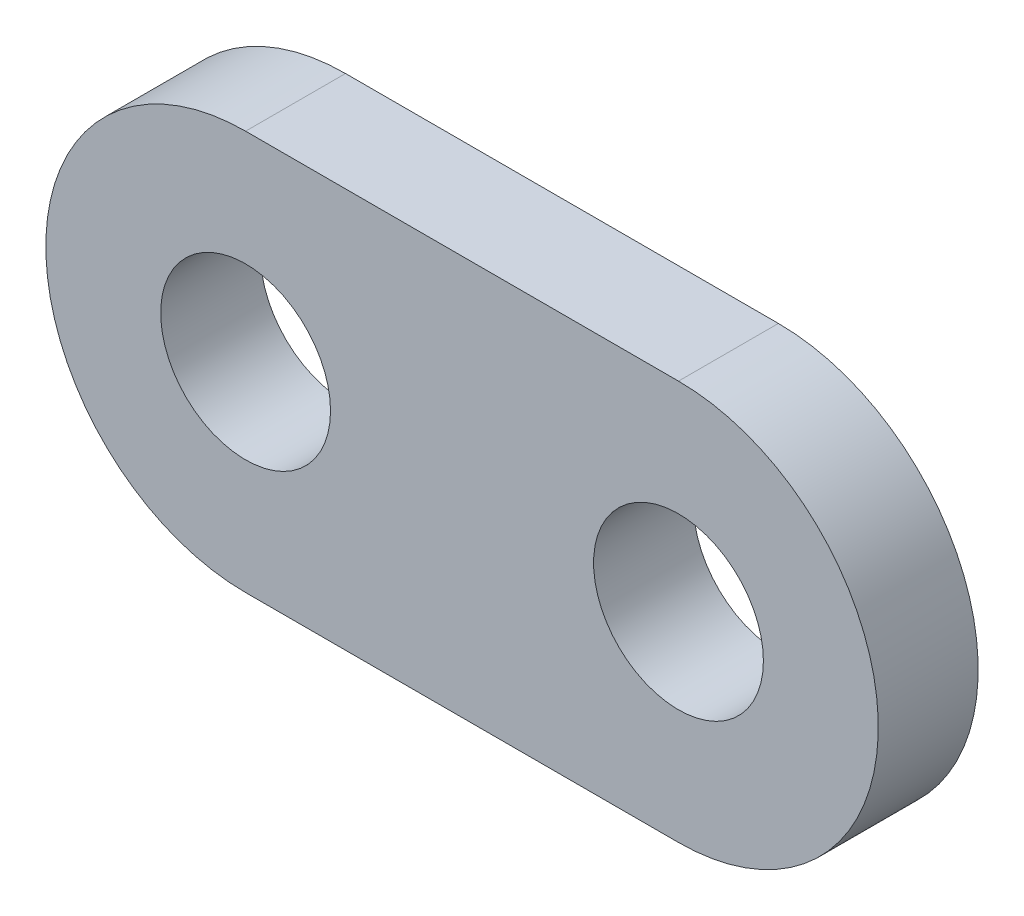
SolidWorks part; units mm, degrees
ref_plane "Ebene vorne" through (0, 0, 0) normal (0, 0, 1) x (1, 0, 0)
ref_plane "Ebene oben" through (0, 0, 0) normal (0, 1, 0) x (1, 0, 0)
ref_plane "Ebene rechts" through (0, 0, 0) normal (1, 0, 0) x (0, 0, -1)
sketch "Model" plane through (0, 0, 0) normal (0, 0, 1) x (1, 0, 0)
  line L0 (19, 12) -> (6, 12)
  line L1 (6, 0) -> (19, 0)
  circle A0 centre (6, 6) radius 2.55
  circle A1 centre (19, 6) radius 2.55
  arc A2 (6, 12) -> (6, 0) centre (6, 6) ccw
  arc A3 (19, 0) -> (19, 12) centre (19, 6) ccw
extrude "Aufsatz-Linear austragen1" add sketch "Model" along normal blind 3
